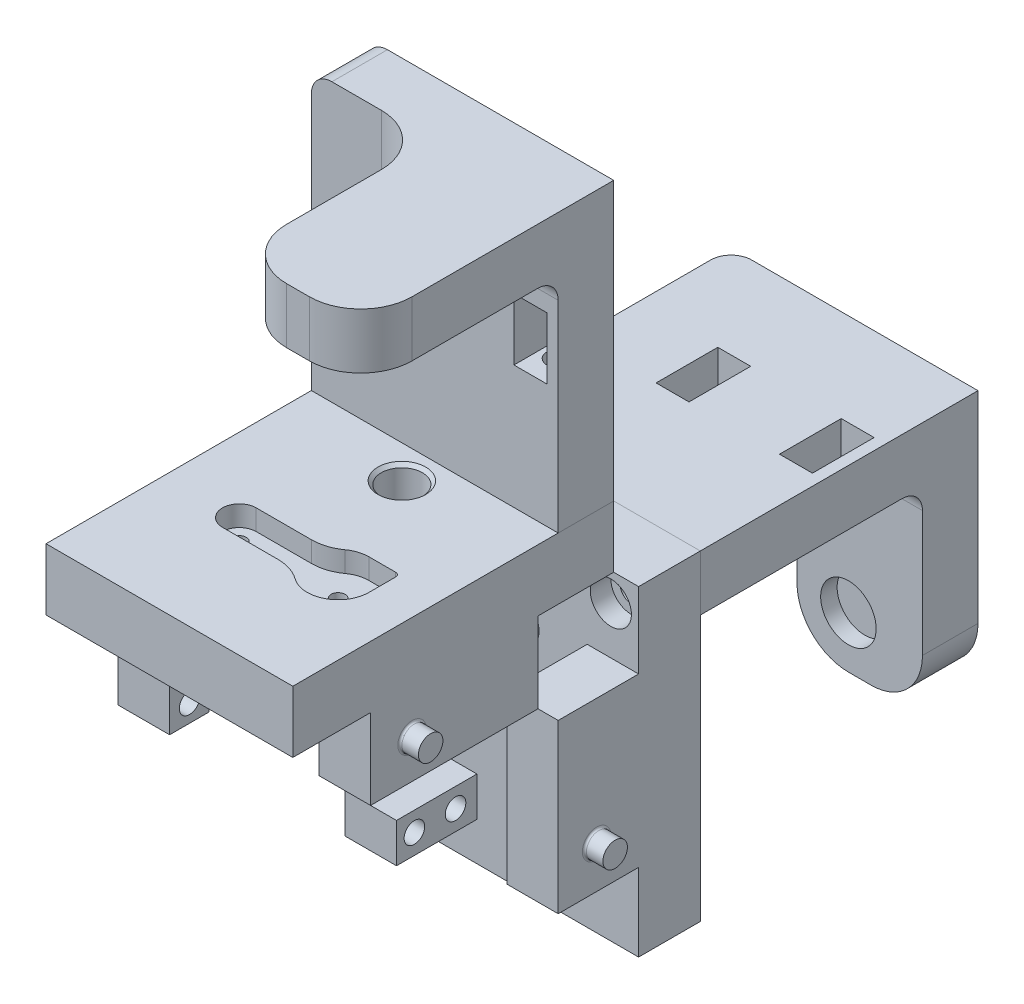
SolidWorks part; units mm, degrees
ref_plane "Front Plane" through (0, 0, 0) normal (0, 0, 1) x (1, 0, 0)
ref_plane "Top Plane" through (0, 0, 0) normal (0, 1, 0) x (1, 0, 0)
ref_plane "Right Plane" through (0, 0, 0) normal (1, 0, 0) x (0, 0, -1)
sketch "Sketch1" plane through (0, 0, 0) normal (0, 1, 0) x (1, 0, 0)
  line L0 (0, 0) -> (12, 0) construction
  line L8 (42, 29) -> (42, 49)
  line L9 (-18, -29) -> (42, -29)
  line L10 (-18, -29) -> (-18, 29)
  line L12 (42, -29) -> (42, 29)
  line L13 (-18, -29) -> (42, 29) construction
  line L14 (-18, 29) -> (42, -29) construction
  line L15 (42, 49) -> (-18, 49)
  line L16 (-18, 49) -> (-18, 29)
  point P7 (12, 0)
  dimension "D1" = 12
  dimension "D2" = 58
  dimension "D3" = 60
  dimension "D4" = 20
extrude "Boss-Extrude1" add sketch "Sketch1" along normal blind 15
sketch "Sketch2" plane through (0, 15, 0) normal (0, 1, 0) x (1, 0, 0)
  line L0 (0, 4) -> (13.4812, 4) construction
  line L1 (13.4812, -4) -> (0, -4) construction
  line L2 (0, 4) -> (13.4812, 4) construction
  line L3 (13.4812, -4) -> (0, -4) construction
  line L10 (13.4812, -4.1) -> (0, -4.1)
  line L11 (0, 4.1) -> (13.4812, 4.1)
  line L12 (31.5, 0) -> (31.5, 6.5)
  line L13 (30.5, 7.5) -> (24, 7.5)
  arc A0 (28.3313, -6) -> (31.3939, -0.3) centre (24, 0) ccw construction
  arc A2 (-4.1, 0) -> (0, -4.1) centre (0, 0) ccw
  arc A3 (13.4812, 4) -> (19.6687, 6) centre (13.4812, 14.5714) ccw construction
  arc A4 (0, 4) -> (-4, 0) centre (0, 0) ccw construction
  arc A5 (-4, 0) -> (0, -4) centre (0, 0) ccw construction
  arc A6 (19.6687, -6) -> (13.4812, -4) centre (13.4812, -14.5714) ccw construction
  arc A11 (13.4812, 4) -> (19.6687, 6) centre (13.4812, 14.5714) ccw construction
  arc A12 (0, 4) -> (-4, 0) centre (0, 0) ccw construction
  arc A13 (-4, 0) -> (0, -4) centre (0, 0) ccw construction
  arc A14 (19.6687, -6) -> (13.4812, -4) centre (13.4812, -14.5714) ccw construction
  arc A16 (19.6687, -6) -> (19.6687, 6) centre (24, 0) ccw construction
  arc A19 (0, 4.1) -> (-4.1, 0) centre (0, 0) ccw
  arc A20 (13.4812, 4.1) -> (19.6102, 6.0811) centre (13.4812, 14.5714) ccw
  arc A21 (19.6102, -6.0811) -> (31.5, 0) centre (24, 0) ccw
  arc A22 (19.6102, -6.0811) -> (13.4812, -4.1) centre (13.4812, -14.5714) ccw
  arc A23 (31.5, 6.5) -> (30.5, 7.5) centre (30.5, 6.5) ccw
  arc A24 (24, 7.5) -> (19.6102, 6.0811) centre (24, 0) ccw
  arc A25 (19.6102, -6.0811) -> (19.6102, 6.0811) centre (24, 0) ccw construction
  dimension "D2" = 1
  dimension "D1" = 0.1
extrude "Cut-Extrude2" cut sketch "Sketch2" against normal blind 5 contours A19 A2 L10 A22 A21 L12 A23 L13 A24 A20 L11
hole_wizard "CBORE for M3 SHCS2" positions "3DSketch2" profile "Sketch11" counterbore size "M3" standard "ANSI Metric" end condition through all
sketch3d "3DSketch2"
  arc A1 (19.6102, 15, 6.0811) -> (31.5, 15, 0) centre (24, 15, 0) ccw construction
  point P14 (24, 22.5, 0)
  point P17 (24, 0, 0)
sketch "Sketch11" plane through (24, 0, 0) normal (1, 0, 0) x (0, 0, -1)
  line L0 (0, 0) -> (0, 15)
  line L1 (0, 15) -> (1.7, 15)
  line L3 (1.7, 15) -> (1.7, 3)
  line L4 (3.25, 3) -> (1.7, 3)
  line L5 (3.25, 3) -> (3.25, 0.025)
  line L6 (3.25, 0.025) -> (3.275, 0)
  line L7 (3.275, 0) -> (0, 0)
  line L8 (-3.25, 0.025) -> (-3.275, 0) construction
  line L11 (0, -6.35) -> (0, 107.95) construction
  dimension "Thru Hole Dia." = 3.4
  dimension "Thru Hole Depth" = 15
  dimension "C'Bore Dia." = 6.5
  dimension "C'Bore Depth" = 3
  dimension "Near C'Sink Dia." = 6.55
  dimension "Near C'Sink Angle" = 90
sketch "Sketch12" plane through (0, 0, 0) normal (0, -1, 0) x (1, 0, 0)
  line L0 (10.1, -30.1) -> (-9.7, -30.1) construction
  line L11 (2.7, -40.15) -> (-9.8, -40.15)
  line L17 (-9.8, 19.65) -> (2.7, 19.65)
  line L18 (-9.8, 19.65) -> (-9.8, 10.1)
  line L19 (-9.8, 10.1) -> (2.7, 10.1)
  line L20 (2.7, 19.65) -> (2.7, 10.1)
  line L21 (-9.8, 10.0887) -> (-9.8, 15.15) construction
  line L22 (10.1, 10.1) -> (-9.7, 10.1) construction
  line L23 (2.7, -40.15) -> (2.7, -30.6)
  line L24 (2.7, -30.6) -> (-9.8, -30.6)
  line L25 (-9.8, -40.15) -> (-9.8, -30.6)
  line L26 (-9.8, -35.15) -> (-9.8, -30.0887) construction
  line L27 (-9.8, 17.15) -> (-13, 17.15) construction
  dimension "D1" = 0.5
  dimension "D2" = 12.5
  dimension "D3" = 2.5
extrude "Boss-Extrude5" add sketch "Sketch12" along normal up to surface (19.55 mm away)
sketch "Sketch13" plane through (-9.8, 0, 0) normal (-1, 0, 0) x (0, 0, 1)
  arc A0 (-36.8729, -16.075) -> (-36.8729, -14.325) centre (-34.8, -15.2) ccw construction
  arc A1 (-36.8729, -6.075) -> (-36.8729, -4.325) centre (-34.8, -5.2) ccw construction
  arc A2 (16.8729, -14.325) -> (16.8729, -16.075) centre (14.8, -15.2) ccw construction
  arc A3 (16.8729, -4.325) -> (16.8729, -6.075) centre (14.8, -5.2) ccw construction
  arc A4 (-36.8729, -16.075) -> (-36.8729, -14.325) centre (-34.8, -15.2) ccw construction
  arc A5 (-36.8729, -6.075) -> (-36.8729, -4.325) centre (-34.8, -5.2) ccw construction
  arc A6 (16.8729, -14.325) -> (16.8729, -16.075) centre (14.8, -15.2) ccw construction
  arc A7 (16.8729, -4.325) -> (16.8729, -6.075) centre (14.8, -5.2) ccw construction
  circle A12 centre (14.8, -5.2) radius 2.5
  circle A13 centre (14.8, -15.2) radius 2.5
  circle A14 centre (-34.8, -5.2) radius 2.5
  circle A15 centre (-34.8, -15.2) radius 2.5
  dimension "D1" = 5
extrude "Cut-Extrude3" cut sketch "Sketch13" against normal through all
sketch "Esquisse1" plane through (0, 15, 0) normal (0, 1, 0) x (1, 0, 0)
  line L8 (16.5697, 0.3) -> (20.0113, 0.3)
  line L9 (20.0113, -0.3) -> (16.5697, -0.3)
  line L10 (31.3939, -0.3) -> (27.9887, -0.3)
  line L11 (19.6687, -6) -> (28.3313, -6)
  line L12 (0, -4) -> (13.4812, -4)
  line L13 (13.4812, 4) -> (0, 4)
  line L14 (28.3313, 6) -> (19.6687, 6)
  line L15 (27.9887, 0.3) -> (31.3939, 0.3)
  line L16 (16.5697, 0.3) -> (20.0113, 0.3) construction
  line L17 (20.0113, -0.3) -> (16.5697, -0.3) construction
  line L18 (31.3939, -0.3) -> (27.9887, -0.3) construction
  line L19 (19.6687, -6) -> (28.3313, -6) construction
  line L20 (0, -4) -> (13.4812, -4) construction
  line L21 (13.4812, 4) -> (0, 4) construction
  line L22 (28.3313, 6) -> (19.6687, 6) construction
  line L23 (27.9887, 0.3) -> (31.3939, 0.3) construction
  arc A10 (27.9887, 0.3) -> (20.0113, 0.3) centre (24, 0) ccw
  arc A11 (16.5697, 0.3) -> (13.6, 0) centre (15.1, 0) ccw
  arc A12 (13.6, 0) -> (16.5697, -0.3) centre (15.1, 0) ccw
  arc A13 (20.0113, -0.3) -> (27.9887, -0.3) centre (24, 0) ccw
  arc A14 (28.3313, -6) -> (31.3939, -0.3) centre (24, 0) ccw
  arc A15 (19.6687, -6) -> (13.4812, -4) centre (13.4812, -14.5714) ccw
  arc A16 (-4, 0) -> (0, -4) centre (0, 0) ccw
  arc A17 (0, 4) -> (-4, 0) centre (0, 0) ccw
  arc A18 (13.4812, 4) -> (19.6687, 6) centre (13.4812, 14.5714) ccw
  arc A19 (31.3939, 0.3) -> (28.3313, 6) centre (24, 0) ccw
  arc A20 (27.9887, 0.3) -> (20.0113, 0.3) centre (24, 0) ccw construction
  arc A21 (16.5697, 0.3) -> (13.6, 0) centre (15.1, 0) ccw construction
  arc A22 (13.6, 0) -> (16.5697, -0.3) centre (15.1, 0) ccw construction
  arc A23 (20.0113, -0.3) -> (27.9887, -0.3) centre (24, 0) ccw construction
  arc A24 (28.3313, -6) -> (31.3939, -0.3) centre (24, 0) ccw construction
  arc A25 (19.6687, -6) -> (13.4812, -4) centre (13.4812, -14.5714) ccw construction
  arc A26 (-4, 0) -> (0, -4) centre (0, 0) ccw construction
  arc A27 (0, 4) -> (-4, 0) centre (0, 0) ccw construction
  arc A28 (13.4812, 4) -> (19.6687, 6) centre (13.4812, 14.5714) ccw construction
  arc A29 (31.3939, 0.3) -> (28.3313, 6) centre (24, 0) ccw construction
  dimension "D1" = 0
hole_wizard "CBORE for M3 Pan Head Machine Screw1" positions "Esquisse3D1" profile "Esquisse2" counterbore size "M3" standard "ANSI Metric" end condition up to next
sketch3d "Esquisse3D1"
  arc A1 (-1.25, 16, 0) -> (1.25, 16, 0) centre (0, 16, 0) ccw construction
  point P12 (0, 0, 0)
  point P20 (0, 14.75, 0)
sketch "Esquisse2" plane through (0, 0, 0) normal (1, 0, 0) x (0, 0, -1)
  line L0 (0, 0) -> (0, 10)
  line L1 (0, 10) -> (1.7, 10)
  line L3 (1.7, 10) -> (1.7, 2.4)
  line L4 (1.7, 2.4) -> (3.5, 2.4)
  line L5 (3.5, 2.4) -> (3.5, 0)
  line L7 (3.5, 0) -> (0, 0)
  line L11 (0, -6.35) -> (0, 107.95) construction
  dimension "Diamètre du perçage jusqu'au prochain" = 3.4
  dimension "Profondeur du perçage jusqu'au prochain" = 10
  dimension "Diamètre du chambrage" = 7
  dimension "Profondeur du chambrage" = 2.4
ref_plane "Plan1" through (24, 0, 0) normal (1, 0, 0) x (0, 0, -1)
ref_plane "Plane1" through (12, 0, 0) normal (1, 0, 0) x (0, 0, -1)
sketch "Sketch14" plane through (0, 49, -49) normal (0, 0, 1) x (1, 0, 0)
  line L0 (42, -34) -> (-18, -34) construction
  line L5 (42, -49) -> (-18, -49)
  line L6 (42, -49) -> (42, 33.5)
  line L7 (42, 33.5) -> (-18, 33.5)
  line L8 (-18, -49) -> (-18, 33.5)
  dimension "D1" = 67.5
extrude "Boss-Extrude6" add sketch "Sketch14" along normal blind 13.5
sketch "Sketch16" plane through (0, 82.5, -132) normal (0, -1, 0) x (1, 0, 0)
  line L6 (42, 96.5) -> (-18, 96.5) construction
  line L7 (11.5, 96.5) -> (42, 96.5)
  line L8 (11.5, 96.5) -> (11.5, 144.5)
  line L9 (11.5, 144.5) -> (42, 144.5)
  line L10 (42, 96.5) -> (42, 144.5)
  line L11 (24, 144.5) -> (24, 132) construction
  circle A0 centre (24, 132) radius 1.7 construction
  dimension "D1" = 12.5
  dimension "D2" = 12.5
extrude "Boss-Extrude7" add sketch "Sketch16" along normal blind 13.5
sketch "Sketch17" plane through (0, 69, -77) normal (0, -1, 0) x (1, 0, 0)
  circle A0 centre (24, 77) radius 6.7469
  arc A1 (31.5, 77) -> (19.6102, 83.0811) centre (24, 77) ccw construction
  dimension "D1" = 13.4937
extrude "Cut-Extrude4" cut sketch "Sketch17" against normal blind 4
hole_wizard "Chambrage pour vis à tête cylindrique à 6 pans creux (ou vis CHC) M51" positions "3DSketch3" profile "Sketch20" counterbore size "M5" standard "Ansi Metric"
sketch3d "3DSketch3"
  line L4 (35.25, 0, -42.25) -> (5.25, 0, -42.25) construction
  line L6 (42, 0, 29) -> (42, 0, -49) construction
  line L11 (42, 0, -49) -> (-18, 0, -49) construction
  point P0 (35.25, 0, -42.25)
  point P2 (5.25, 0, -42.25)
  point P34 (11.7125, 0, -42.25)
  dimension "D1" = 6.75
  dimension "D3" = 30
  dimension "D2" = 6.75
sketch "Sketch20" plane through (35.25, 0, -42.25) normal (1, 0, 0) x (0, 0, -1)
  line L0 (0, 0) -> (0, 46.6524)
  line L1 (0, 46.6524) -> (2.75, 45)
  line L2 (2.75, 45) -> (2.75, 5)
  line L3 (2.75, 5) -> (5, 5)
  line L4 (5, 5) -> (5, 0)
  line L5 (5, 0) -> (0, 0)
  line L10 (0, 46.6524) -> (-2.75, 45) construction
  line L11 (0, -6.35) -> (0, 107.95) construction
  dimension "Diamètre du perçage" = 5.5
  dimension "Profondeur du perçage" = 45
  dimension "Diamètre du chambrage" = 10
  dimension "Profondeur du chambrage" = 5
  dimension "Angle de pointe" = 118
sketch "Sketch22" plane through (0, 0, 0) normal (0, -1, 0) x (1, 0, 0)
  line L0 (42, 29) -> (42, -49) construction
  line L1 (42, -30.6) -> (29.5, -30.6)
  line L2 (42, -30.6) -> (42, 10.1)
  line L3 (42, 10.1) -> (29.5, 10.1)
  line L4 (29.5, -30.6) -> (29.5, 10.1)
  line L9 (2.7, -30.6) -> (-9.8, -30.6) construction
  line L10 (-9.8, 10.1) -> (2.7, 10.1) construction
  dimension "D1" = 12.5
extrude "Boss-Extrude8" add sketch "Sketch22" along normal up to surface (19.55 mm away) up to face at (-3.55, -19.55, -35.375)
sketch "Sketch23" plane through (42, 0, 0) normal (1, 0, 0) x (0, 0, -1)
  circle A0 centre (0, -10.2) radius 2.9766
  circle A1 centre (0, -10.2) radius 6 construction
  dimension "D1" = 5.9531
extrude "Boss-Extrude9" add sketch "Sketch23" along normal blind 4.5
sketch "Sketch24" plane through (42, 0, 0) normal (1, 0, 0) x (0, 0, -1)
  line L0 (49, 15) -> (35.5, 15)
  line L3 (49, 82.5) -> (49, 0) construction
fillet "Fillet2" radius 0.5 1 edges at (42, -10.2, 2.9766)
sketch3d "Esquisse3D2"
  line L0 (35.25, 0, -42.25) -> (35.25, 82.5, -42.25) construction
  line L1 (35.25, 5, -42.25) -> (35.25, 0, -42.25) construction
  line L2 (35.25, 45, -42.25) -> (35.25, 5, -42.25) construction
  line L3 (5.25, 0, -42.25) -> (5.25, 82.5, -42.25) construction
  line L4 (5.25, 5, -42.25) -> (5.25, 0, -42.25) construction
  circle A1 centre (35.25, 0, -42.25) radius 5 construction
  point P12 (35.25, -5, -42.25)
sketch "Esquisse6" plane through (0, 0, -49) normal (0, 0, 1) x (1, 0, 0)
  line L0 (42, 0) -> (-18, 0) construction
  line L1 (39.25, 60) -> (31.25, 60)
  line L2 (39.25, 60) -> (39.25, 45)
  line L3 (39.25, 45) -> (31.25, 45)
  line L4 (31.25, 60) -> (31.25, 45)
  line L5 (1.25, 60) -> (9.25, 60)
  line L6 (1.25, 60) -> (1.25, 45)
  line L7 (1.25, 45) -> (9.25, 45)
  line L8 (9.25, 60) -> (9.25, 45)
  line L15 (35.25, 0) -> (35.25, 82.5) construction
  line L16 (5.25, 0) -> (5.25, 82.5) construction
  point P12 (35.25, 45)
  point P17 (5.25, 45)
  dimension "D1" = 8
  dimension "D2" = 45
  dimension "D3" = 15
extrude "Enlèv. mat.-Extru.4" cut sketch "Esquisse6" along normal through all
fillet "Congé1" radius 12.5 3 edges at (11.5, 75.75, -35.5) (11.5, 75.75, 12.5) (42, 75.75, 12.5)
fillet "Congé2" radius 5 2 edges at (-18, 82.5, -42.25) (20.5, 69, -35.5)
sketch "Esquisse7" plane through (0, 0, 0) normal (0, -1, 0) x (1, 0, 0)
  circle A0 centre (5.25, -42.25) radius 5
  arc A1 (0.7124, -40.15) -> (2.7, -37.9491) centre (5.25, -42.25) ccw construction
extrude "Enlèv. mat.-Extru.5" cut sketch "Esquisse7" along normal through all
split "Split3" trim tools "Sketch24" bodies to split 155 resulting bodies 144 145
ref_plane "Plan2" through (0, -27.525, -27.525) normal (0, -0.7071, -0.7071) x (-1, 0, 0)
sketch "Esquisse4" plane through (0, 15, 0) normal (0, 1, 0) x (1, 0, 0)
  line L2 (12, 27.5) -> (12, 35.5) construction
  line L3 (-18, 35.5) -> (42, 35.5) construction
  circle A0 centre (12, 27.5) radius 5
  dimension "D1" = 10
  dimension "D2" = 8
extrude "Enlèv. mat.-Extru.2" cut sketch "Esquisse4" against normal up to next (15 mm away)
chamfer "Chanfrein1" distance 0.8 angle 45 2 edges at (12, 15, -22.5) (12, 0, -22.5)
mirror "Symétrie1" about plane through (0, -27.525, -27.525) normal (0, -0.7071, -0.7071) of bodies 144 150 147 145
